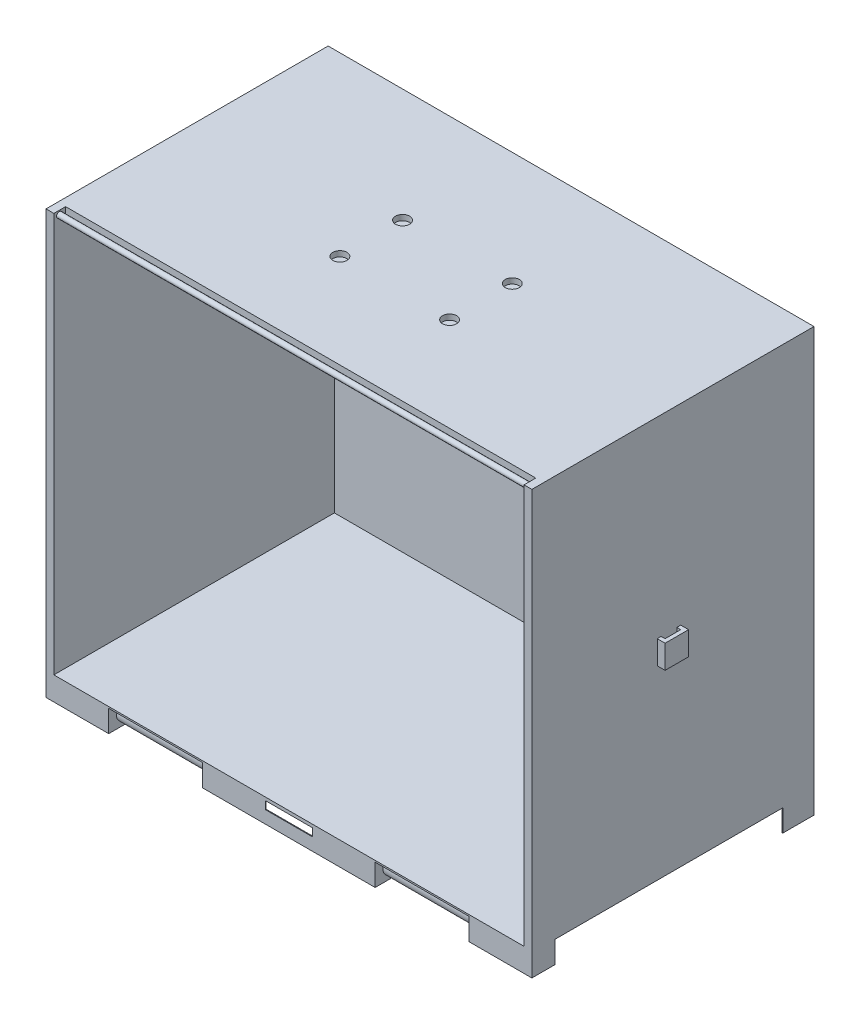
SolidWorks part; units mm, degrees
material "Polyetheretherketone (PEEK)"
ref_plane "Front Plane" through (0, 0, 0) normal (0, 0, 1) x (1, 0, 0)
ref_plane "Top Plane" through (0, 0, 0) normal (0, 1, 0) x (1, 0, 0)
ref_plane "Right Plane" through (0, 0, 0) normal (1, 0, 0) x (0, 0, -1)
sketch "Sketch1" plane through (0, 0, 0) normal (0, 0, 1) x (1, 0, 0)
  line L1 (-300, 250) -> (300, 250)
  line L2 (-300, 250) -> (-300, -250)
  line L3 (-300, -250) -> (300, -250)
  line L4 (300, 250) -> (300, -250)
  line L5 (-300, 250) -> (300, -250) construction
  line L6 (-300, -250) -> (300, 250) construction
  point P0 (0, 0)
  dimension "D1" = 500
  dimension "D2" = 600
extrude "Boss-Extrude1" add sketch "Sketch1" along normal mid plane 350
shell "Shell1" thickness 10
sketch "Sketch3" plane through (0, -260, 0) normal (0, -1, 0) x (1, 0, 0)
  line L4 (-310, -185) -> (310, -185)
  line L5 (310, -185) -> (310, 175)
  line L6 (310, 175) -> (-310, 175)
  line L7 (-310, 175) -> (-310, -185)
  line L8 (-310, -185) -> (310, -185)
  line L9 (310, -185) -> (310, 175)
  line L10 (310, 175) -> (-310, 175)
  line L11 (-310, 175) -> (-310, -185)
  dimension "D1" = 0
extrude "Boss-Extrude2" add sketch "Sketch3" along normal blind 20
sketch "Sketch5" plane through (0, -280, 0) normal (0, -1, 0) x (1, 0, 0)
  line L0 (310, 175) -> (-310, 175) construction
  line L1 (-230, 25) -> (-110, 25)
  line L2 (-230, 25) -> (-230, 175)
  line L3 (-230, 175) -> (-110, 175)
  line L4 (-110, 25) -> (-110, 175)
  line L5 (-230, 25) -> (-110, 175) construction
  line L6 (-230, 175) -> (-110, 25) construction
  line L7 (-310, 175) -> (-310, -185) construction
  line L8 (0, -55) -> (0, 55) construction
  line L9 (230, 175) -> (110, 25) construction
  line L10 (230, 25) -> (110, 175) construction
  line L11 (110, 25) -> (110, 175)
  line L12 (230, 175) -> (110, 175)
  line L13 (230, 25) -> (230, 175)
  line L14 (230, 25) -> (110, 25)
  line L16 (-280, -260) -> (-280, -110)
  line L17 (280, -110) -> (160, -110)
  line L18 (280, -260) -> (160, -110) construction
  line L19 (-160, -260) -> (-160, -110)
  line L20 (280, -260) -> (280, -110)
  line L21 (-280, -110) -> (-160, -110)
  line L22 (-280, -260) -> (-160, -260)
  line L23 (-280, -260) -> (-160, -110) construction
  line L24 (280, -110) -> (160, -260) construction
  line L25 (160, -260) -> (160, -110)
  line L26 (280, -260) -> (160, -260)
  line L27 (-280, -110) -> (-160, -260) construction
  point P0 (-170, 100)
  point P11 (170, 100)
  point P16 (-220, -185)
  point P21 (220, -185)
  dimension "D1" = 80
  dimension "D2" = 120
  dimension "D3" = 150
extrude "Cut-Extrude1" cut sketch "Sketch5" against normal blind 50
sketch "Sketch8" plane through (0, 0, 0) normal (0, 1, 0) x (1, 0, 0)
  line L0 (-310, 10) -> (-315, 10)
  line L1 (-310, -175) -> (-310, 185) construction
  line L2 (-315, 10) -> (-315, -10)
  line L3 (-315, -10) -> (-310, -10)
  line L4 (-310, 15) -> (-320, 15)
  line L5 (-320, 15) -> (-320, -15)
  line L6 (-320, -15) -> (-310, -15)
  line L7 (-310, 15) -> (-310, 10)
  line L8 (-310, -10) -> (-310, -15)
  point P5 (-315, 0)
  dimension "D1" = 5
  dimension "D2" = 20
  dimension "D3" = 5
extrude "Boss-Extrude3" add sketch "Sketch8" along normal mid plane 30
sketch "Sketch9" plane through (-110, 0, 0) normal (-1, 0, 0) x (0, 0, 1)
  line L0 (25, -280) -> (175, -280) construction
  line L2 (175, -250) -> (175, -280) construction
  line L4 (-185, -280) -> (-110, -280) construction
  line L5 (-185, -230) -> (-185, -280) construction
  circle A0 centre (155, -265) radius 10
  circle A2 centre (-165, -265) radius 10
  circle A3 centre (-165, -265) radius 9.2069
  circle A4 centre (155, -265) radius 8.805
  dimension "D1" = 20
  dimension "D5" = 20
  dimension "D2" = 15
  dimension "D3" = 20
  dimension "D4" = 15
  dimension "D6" = 20
extrude "Boss-Extrude4" add sketch "Sketch9" along normal blind 180
mirror "Mirror1" about plane through (0, 0, 0) normal (1, 0, 0) of "Boss-Extrude3", "Boss-Extrude4"
sketch "Sketch17" plane through (0, 260, 0) normal (0, 1, 0) x (1, 0, 0)
  line L0 (-194.2233, 185) -> (-204.2233, 185)
  line L1 (310, 185) -> (-310, 185) construction
  line L2 (-204.2233, 185) -> (-204.2233, 191.5405)
  line L3 (-204.2233, 191.5405) -> (-159.461, 191.5405)
  line L4 (-159.461, 191.5405) -> (-159.461, 185)
  line L5 (-159.461, 185) -> (-169.461, 185)
  line L6 (-169.461, 185) -> (-169.461, 188.4429)
  line L7 (-169.461, 188.4429) -> (-194.2233, 188.4429)
  line L8 (-194.2233, 188.4429) -> (-194.2233, 185)
  line L9 (0, -198) -> (0, 198) construction
  line L10 (194.2233, 188.4429) -> (194.2233, 185)
  line L11 (169.461, 188.4429) -> (194.2233, 188.4429)
  line L12 (169.461, 185) -> (169.461, 188.4429)
  line L13 (159.461, 185) -> (169.461, 185)
  line L14 (159.461, 191.5405) -> (159.461, 185)
  line L15 (204.2233, 191.5405) -> (159.461, 191.5405)
  line L16 (204.2233, 185) -> (204.2233, 191.5405)
  line L17 (194.2233, 185) -> (204.2233, 185)
  dimension "D1" = 10
  dimension "D2" = 10
extrude "Boss-Extrude8" add sketch "Sketch17" along normal mid plane 20 from surface at -260 starting at plane "Top Plane"
sketch "Sketch147" plane through (0, 260, 0) normal (0, 1, 0) x (1, 0, 0)
  line L0 (-300, -175) -> (-300, -160)
  line L1 (310, -175) -> (-310, -175) construction
  line L2 (-300, -160) -> (300, -160)
  line L3 (300, -160) -> (300, -175)
  line L4 (-310, -175) -> (-310, 185) construction
  line L5 (310, -175) -> (310, 185) construction
  line L6 (-300, -175) -> (300, -175)
  dimension "D1" = 10
  dimension "D2" = 10
  dimension "D3" = 15
extrude "Cut-Extrude2" cut sketch "Sketch147" against normal blind 10
sketch "Sketch148" plane through (-300, 0, 0) normal (1, 0, 0) x (0, 0, -1)
  line L0 (-175, -280) -> (-175, 260) construction
  line L1 (-175, 260) -> (185, 260) construction
  circle A0 centre (-168, 255) radius 3.5
  dimension "D1" = 7
  dimension "D2" = 7
  dimension "D3" = 5
extrude "Boss-Extrude10" add sketch "Sketch148" along normal up to surface (600 mm away) up to face at (300, 86.6667, 53.3333)
sketch "Sketch149" plane through (0, 260, 0) normal (0, 1, 0) x (1, 0, 0)
  line L1 (-50, 50) -> (50, 50) construction
  line L2 (-50, 50) -> (-50, -50) construction
  line L3 (-50, -50) -> (50, -50) construction
  line L4 (50, 50) -> (50, -50) construction
  line L5 (-50, 50) -> (50, -50) construction
  line L6 (-50, -50) -> (50, 50) construction
  circle A0 centre (-70, 40) radius 9
  point P0 (0, 0)
  point P8 (-61, 40)
  point P9 (-70, 49)
  dimension "D3" = 18
  dimension "D1" = 100
  dimension "D2" = 20
  dimension "D4" = 1
extrude "Cut-Extrude3" cut sketch "Sketch149" against normal blind 7
mirror "Mirror3" about plane through (0, 0, 0) normal (0, 0, 1) of "Cut-Extrude3" second plane through (0, 0, 0) second plane normal (1, 0, 0)
sketch "Sketch150" plane through (0, 0, 175) normal (0, 0, 1) x (1, 0, 0)
  line L0 (-300, -250) -> (-280, -250) construction
  line L1 (-30, -254) -> (30, -254)
  line L2 (-30, -254) -> (-30, -264)
  line L3 (-30, -264) -> (30, -264)
  line L4 (30, -254) -> (30, -264)
  line L5 (-30, -254) -> (30, -264) construction
  line L6 (-30, -264) -> (30, -254) construction
  point P0 (0, -259)
  dimension "D1" = 4
  dimension "D2" = 10
  dimension "D3" = 60
extrude "Cut-Extrude4" cut sketch "Sketch150" against normal blind 30
sketch "Sketch154" plane through (0, -280, 0) normal (0, -1, 0) x (1, 0, 0)
  line L0 (231, 174) -> (231, 24)
  line L1 (231, 24) -> (109, 24)
  line L2 (109, 24) -> (109, 174)
  line L3 (109, 174) -> (-109, 174)
  line L4 (-109, 174) -> (-109, 24)
  line L5 (-109, 24) -> (-231, 24)
  line L6 (-231, 24) -> (-231, 174)
  line L7 (-231, 174) -> (-309, 174)
  line L8 (-309, 174) -> (-309, -184)
  line L9 (-309, -184) -> (-281, -184)
  line L10 (-281, -184) -> (-281, -109)
  line L11 (-281, -109) -> (-159, -109)
  line L12 (-159, -109) -> (-159, -184)
  line L13 (-159, -184) -> (159, -184)
  line L14 (159, -184) -> (159, -109)
  line L15 (159, -109) -> (281, -109)
  line L16 (281, -109) -> (281, -184)
  line L17 (281, -184) -> (309, -184)
  line L18 (309, -184) -> (309, 174)
  line L19 (309, 174) -> (231, 174)
  line L20 (230, 175) -> (230, 25)
  line L21 (230, 25) -> (110, 25)
  line L22 (110, 25) -> (110, 175)
  line L23 (110, 175) -> (-110, 175)
  line L24 (-110, 175) -> (-110, 25)
  line L25 (-110, 25) -> (-230, 25)
  line L26 (-230, 25) -> (-230, 175)
  line L27 (-230, 175) -> (-310, 175)
  line L28 (-310, 175) -> (-310, -185)
  line L29 (-310, -185) -> (-280, -185)
  line L30 (-280, -185) -> (-280, -110)
  line L31 (-280, -110) -> (-160, -110)
  line L32 (-160, -110) -> (-160, -185)
  line L33 (-160, -185) -> (160, -185)
  line L34 (160, -185) -> (160, -110)
  line L35 (160, -110) -> (280, -110)
  line L36 (280, -110) -> (280, -185)
  line L37 (280, -185) -> (310, -185)
  line L38 (310, -185) -> (310, 175)
  line L39 (310, 175) -> (230, 175)
  line L40 (230, 175) -> (230, 25)
  line L41 (230, 25) -> (110, 25)
  line L42 (110, 25) -> (110, 175)
  line L43 (110, 175) -> (-110, 175)
  line L44 (-110, 175) -> (-110, 25)
  line L45 (-110, 25) -> (-230, 25)
  line L46 (-230, 25) -> (-230, 175)
  line L47 (-230, 175) -> (-310, 175)
  line L48 (-310, 175) -> (-310, -185)
  line L49 (-310, -185) -> (-280, -185)
  line L50 (-280, -185) -> (-280, -110)
  line L51 (-280, -110) -> (-160, -110)
  line L52 (-160, -110) -> (-160, -185)
  line L53 (-160, -185) -> (160, -185)
  line L54 (160, -185) -> (160, -110)
  line L55 (160, -110) -> (280, -110)
  line L56 (280, -110) -> (280, -185)
  line L57 (280, -185) -> (310, -185)
  line L58 (310, -185) -> (310, 175)
  line L59 (310, 175) -> (230, 175)
  dimension "D1" = 0
  dimension "D2" = 1
extrude "Cut-Extrude10" cut sketch "Sketch154" against normal blind 28 contours L18 L19 L0 L1 L2 L3 L4 L5 L6 L7 L8 L9 L10 L11 L12 L13 L14 L15 L16 L17
sketch "Sketch155" plane through (-310, 0, 0) normal (-1, 0, 0) x (0, 0, 1)
  line L0 (175, -280) -> (-185, -280) construction
  line L1 (-145.2448, -252) -> (145.2448, -252)
  line L2 (-145.2448, -252) -> (-145.2448, -280)
  line L3 (-145.2448, -280) -> (145.2448, -280)
  line L4 (145.2448, -252) -> (145.2448, -280)
  line L5 (-145.2448, -252) -> (145.2448, -280) construction
  line L6 (-145.2448, -280) -> (145.2448, -252) construction
  point P0 (0, -266)
  dimension "D1" = 28
extrude "Cut-Extrude11" cut sketch "Sketch155" against normal through all
sketch "Sketch157" plane through (-230, 0, 0) normal (1, 0, 0) x (0, 0, -1)
  line L0 (-145.2448, -252) -> (-175, -252)
  line L1 (-175, -250) -> (-175, -280) construction
  line L2 (-175, -252) -> (-175, -250)
  line L3 (-175, -250) -> (-25, -250)
  line L4 (-25, -250) -> (-25, -252)
  line L5 (-145.2448, -252) -> (-25, -252) construction
  line L13 (-175, -280) -> (-145.2448, -280)
  line L14 (-145.2448, -280) -> (-145.2448, -267.199)
  line L15 (-145.2448, -262.801) -> (-145.2448, -252)
  line L16 (-145.2448, -252) -> (-25, -252)
  line L17 (-25, -252) -> (-25, -250)
  line L18 (-25, -250) -> (-175, -250)
  line L19 (-175, -250) -> (-175, -280)
  line L23 (-145.2448, -252) -> (-25, -252)
  arc A1 (-145.2448, -262.801) -> (-145.2448, -267.199) centre (-155, -265) ccw
  dimension "D1" = 0
extrude "Boss-Extrude11" add sketch "Sketch157" along normal blind 488
sketch "Sketch159" plane through (160, 0, 0) normal (1, 0, 0) x (0, 0, -1)
  line L0 (145.2448, -252) -> (185, -252)
  line L1 (185, -280) -> (185, 260) construction
  line L2 (145.2448, -252) -> (110, -252)
  line L3 (110, -252) -> (110, -250)
  line L4 (110, -250) -> (175, -250)
  line L5 (175, -250) -> (175, -230)
  line L6 (175, -230) -> (185, -230)
  line L7 (185, -230) -> (185, -252)
extrude "Boss-Extrude12" add sketch "Sketch159" along normal blind 125 and the other way blind 445
sketch "Sketch160" plane through (0, 0, -175) normal (0, 0, 1) x (1, 0, 0)
  line L4 (-300, -250) -> (300, -250)
  line L5 (300, -250) -> (300, 250)
  line L6 (300, 250) -> (-300, 250)
  line L7 (-300, 250) -> (-300, -250)
  line L8 (-300, -250) -> (300, -250)
  line L9 (300, -250) -> (300, 250)
  line L10 (300, 250) -> (-300, 250)
  line L11 (-300, 250) -> (-300, -250)
  dimension "D1" = 0
extrude "Cut-Extrude12" cut sketch "Sketch160" against normal blind 8
